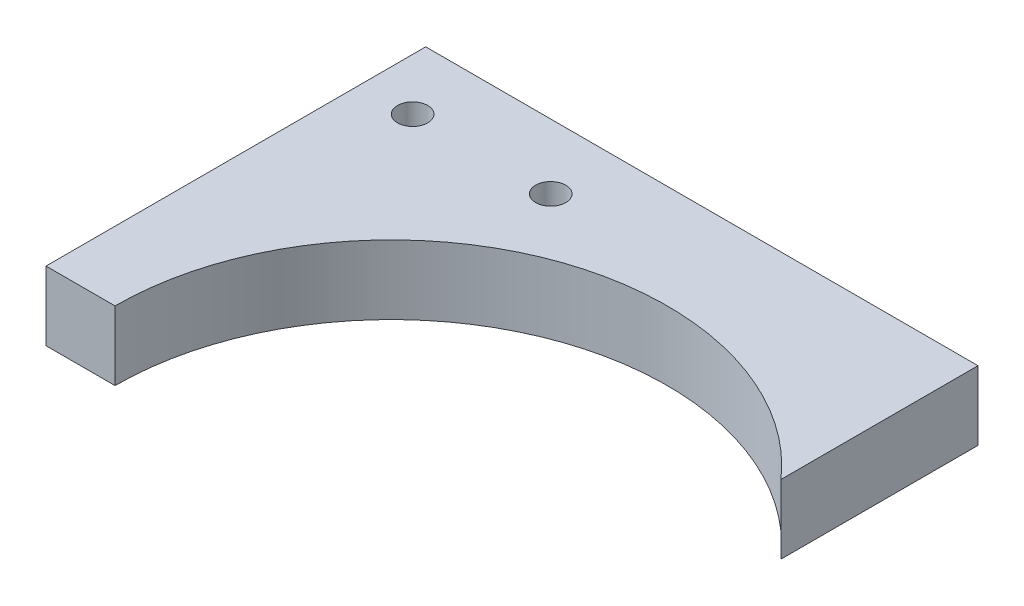
SolidWorks part; units mm, degrees
material "Beech"
ref_plane "Front Plane" through (0, 0, 0) normal (0, 0, 1) x (1, 0, 0)
ref_plane "Top Plane" through (0, 0, 0) normal (0, 1, 0) x (1, 0, 0)
ref_plane "Right Plane" through (0, 0, 0) normal (1, 0, 0) x (0, 0, -1)
sketch "Sketch1" plane through (0, 0, 0) normal (0, 1, 0) x (1, 0, 0)
  line L1 (0, 0) -> (304.8, 0)
  line L2 (0, 0) -> (0, 304.8)
  line L3 (0, 304.8) -> (304.8, 304.8)
  line L4 (304.8, 0) -> (304.8, 304.8)
  dimension "D1" = 304.8
  dimension "D2" = 304.8
extrude "Boss-Extrude1" add sketch "Sketch1" along normal blind 6.35
sketch "Sketch2" plane through (0, 6.35, 0) normal (0, 1, 0) x (1, 0, 0)
  line L1 (304.8, 304.8) -> (0, 304.8) construction
  line L2 (50.8, 304.8) -> (50.8, 269.875)
  line L3 (50.8, 269.875) -> (0, 269.875)
  line L4 (0, 304.8) -> (0, 0) construction
  line L6 (50.8, 304.8) -> (304.8, 304.8)
  line L7 (304.8, 304.8) -> (304.8, 0)
  line L8 (304.8, 0) -> (0, 0)
  line L9 (0, 0) -> (0, 269.875)
extrude "Cut-Extrude1" cut sketch "Sketch2" against normal through all
sketch "Sketch3" plane through (0, 6.35, 0) normal (0, 1, 0) x (1, 0, 0)
  line L0 (50.8, 269.875) -> (0, 269.875) construction
  line L1 (0, 304.8) -> (0, 269.875) construction
  circle A0 centre (31.75, 269.875) radius 25.4
  point P0 (31.75, 269.875)
  dimension "D2" = 50.8
  dimension "D1" = 31.75
extrude "Cut-Extrude2" cut sketch "Sketch3" against normal through all
sketch "Sketch4" plane through (0, 6.35, 0) normal (0, 1, 0) x (1, 0, 0)
  line L0 (0, 304.8) -> (0, 269.875) construction
  circle A0 centre (4.7625, 298.8335) radius 1.3891
  circle A1 centre (17.4625, 298.8335) radius 1.3891
  dimension "D1" = 2.7781
  dimension "D2" = 2.7781
  dimension "D3" = 4.7625
  dimension "D4" = 17.4625
extrude "Cut-Extrude3" cut sketch "Sketch4" against normal through all
